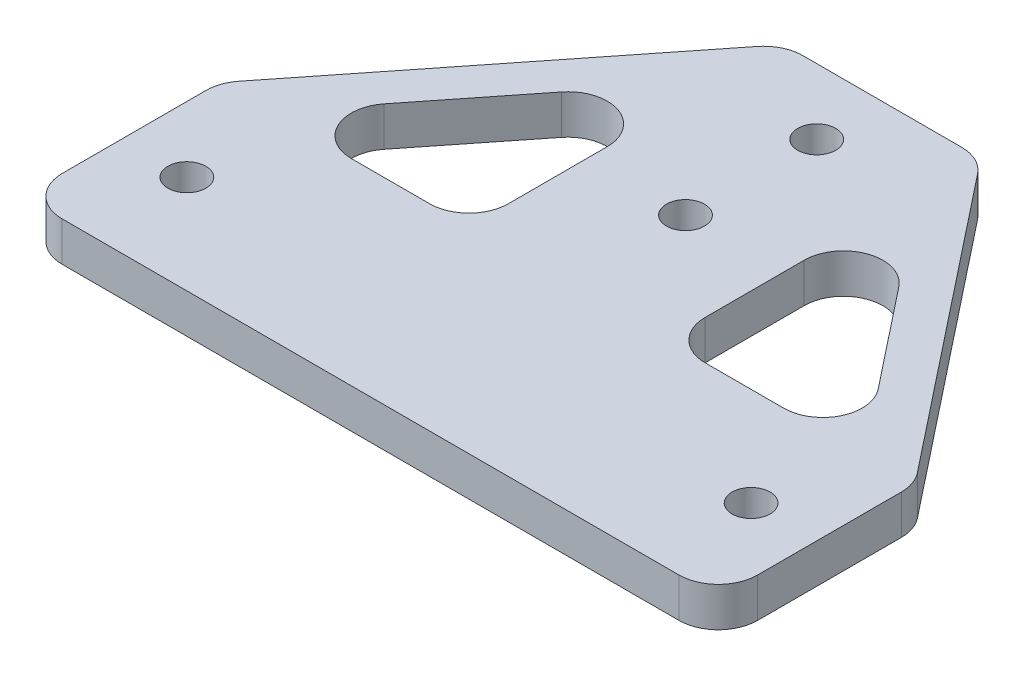
SolidWorks part; units mm, degrees
material "Thornel Mat VMA"
ref_plane "前视基准面" through (0, 0, 0) normal (0, 0, 1) x (1, 0, 0)
ref_plane "上视基准面" through (0, 0, 0) normal (0, 1, 0) x (1, 0, 0)
ref_plane "右视基准面" through (0, 0, 0) normal (1, 0, 0) x (0, 0, -1)
other "Configuration Table"
sketch "草图1" plane through (0, 0, 0) normal (0, 1, 0) x (1, 0, 0)
  line L0 (0, 31.117) -> (0, -29.5669) construction
  line L1 (-26.5, -7.5) -> (26.5, -7.5)
  line L2 (-26.5, -7.5) -> (-26.5, 7.5)
  line L3 (-26.5, 7.5) -> (26.5, 7.5) construction
  line L4 (26.5, -7.5) -> (26.5, 7.5)
  line L5 (-26.5, -7.5) -> (26.5, 7.5) construction
  line L6 (-26.5, 7.5) -> (26.5, -7.5) construction
  line L7 (-7.5, -7.5) -> (7.5, -7.5)
  line L8 (-7.5, -7.5) -> (-7.5, 31.5) construction
  line L9 (-7.5, 31.5) -> (7.5, 31.5)
  line L10 (7.5, -7.5) -> (7.5, 31.5) construction
  line L11 (-41.1018, 0) -> (44.7948, 0) construction
  line L12 (-26.5, 7.5) -> (-7.5, 31.5)
  line L13 (7.5, 31.5) -> (26.5, 7.5)
  line L14 (-7.5, 26.6668) -> (-22.6737, 7.5)
  line L15 (-22.6737, 7.5) -> (-7.5, 7.5)
  line L16 (-7.5, 7.5) -> (-7.5, 26.6668)
  line L17 (7.5, 26.6668) -> (22.6737, 7.5)
  line L18 (22.6737, 7.5) -> (7.5, 7.5)
  line L19 (7.5, 7.5) -> (7.5, 26.6668)
  circle A0 centre (-21.5, 0) radius 1.45
  circle A1 centre (21.5, 0) radius 1.45
  circle A2 centre (0, 16.5) radius 1.45
  circle A3 centre (0, 26.5) radius 1.45
  point P0 (0, 0)
  dimension "D3" = 14
  dimension "D5" = 5
  dimension "D6" = 2.9
  dimension "D7" = 9
  dimension "D8" = 10
  dimension "D9" = 5
  dimension "D1" = 15
  dimension "D2" = 15
  dimension "D4" = 14
  dimension "D10" = 3
  dimension "D11" = 3
extrude "凸台-拉伸1" add sketch "草图1" along normal blind 3 contours L13 L9 L12 L2 L1 L4 A3 A2 A1 A0 L16 L15 L14 L18 L19 L17
fillet "圆角2" radius 3 12 edges at (22.6737, 1.5, -7.5) (7.5, 1.5, -26.6668) (26.5, 1.5, 7.5) (-26.5, 1.5, 7.5) (-26.5, 1.5, -7.5) (-7.5, 1.5, -31.5) (7.5, 1.5, -31.5) (-7.5, 1.5, -26.6668) (-22.6737, 1.5, -7.5) (-7.5, 1.5, -7.5) (26.5, 1.5, -7.5) (7.5, 1.5, -7.5)
